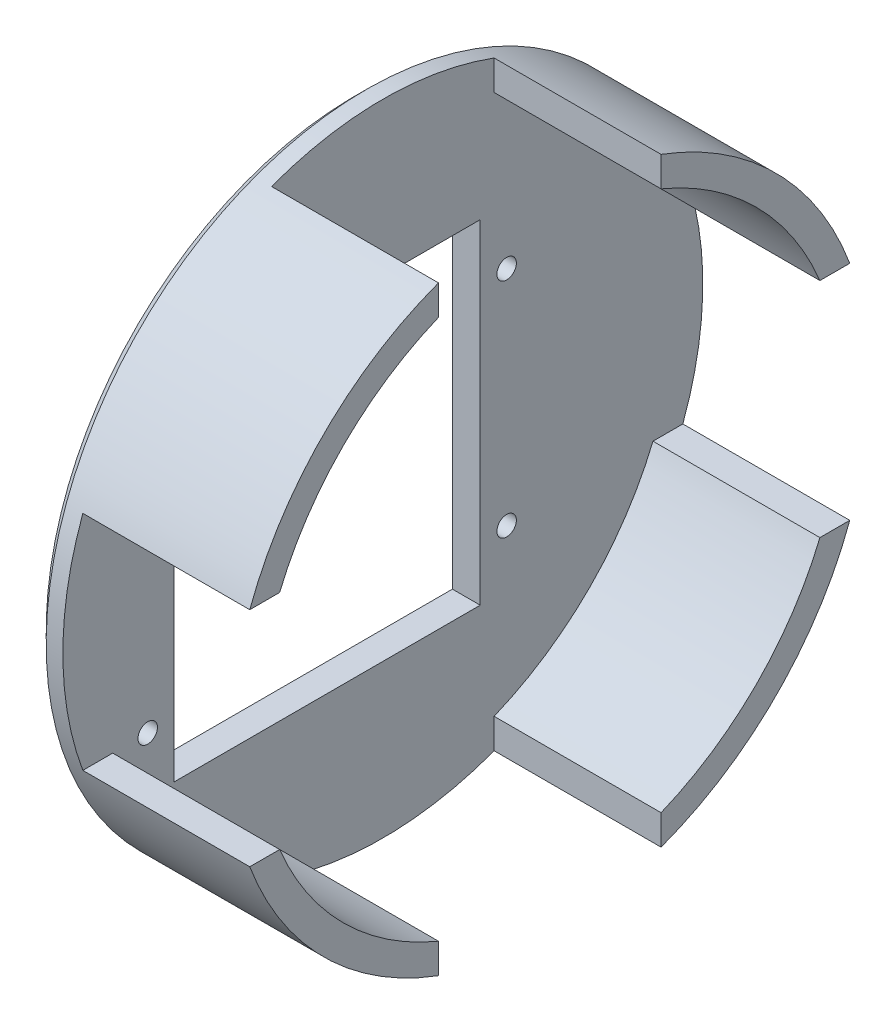
SolidWorks part; units mm, degrees
material "ﾎﾟﾘｴﾁﾚﾝｲﾐﾝ(PEI)"
ref_plane "正面" through (0, 0, 0) normal (0, 0, 1) x (1, 0, 0)
ref_plane "平面" through (0, 0, 0) normal (0, 1, 0) x (1, 0, 0)
ref_plane "右側面" through (0, 0, 0) normal (1, 0, 0) x (0, 0, -1)
sketch "ｽｹｯﾁ1" plane through (0, 0, 0) normal (1, 0, 0) x (0, 0, -1)
  circle A4 centre (0, 0) radius 57.5
  dimension "D4" = 115
extrude "ﾎﾞｽ - 押し出し1" add sketch "ｽｹｯﾁ1" along normal blind 5
sketch "ｽｹｯﾁ2" plane through (5, 0, 0) normal (1, 0, 0) x (0, 0, -1)
  circle A0 centre (0, 0) radius 52.5
  circle A1 centre (0, 0) radius 57.5
  circle A2 centre (0, 0) radius 57.5
  dimension "D1" = 0
  dimension "D2" = 5
extrude "ﾎﾞｽ - 押し出し2" add sketch "ｽｹｯﾁ2" along normal blind 30
sketch "ｽｹｯﾁ3" plane through (5, 0, 0) normal (1, 0, 0) x (0, 0, -1)
  line L0 (0, 0) -> (-10, 0) construction
  line L1 (-10, 20) -> (-10, -20) construction
  line L2 (22.25, 20) -> (-42.25, 20) construction
  line L3 (22.25, 20) -> (22.25, -20) construction
  line L4 (22.25, -20) -> (-42.25, -20) construction
  line L5 (-42.25, 20) -> (-42.25, -20) construction
  line L6 (22.25, 20) -> (-42.25, -20) construction
  line L7 (22.25, -20) -> (-42.25, 20) construction
  line L8 (-42.25, 0) -> (22.25, 0) construction
  line L14 (-37.5, 30) -> (17.5, 30)
  line L15 (-37.5, 30) -> (-37.5, -30)
  line L16 (-37.5, -30) -> (17.5, -30)
  line L17 (17.5, 30) -> (17.5, -30)
  line L18 (-37.5, 30) -> (17.5, -30) construction
  line L19 (-37.5, -30) -> (17.5, 30) construction
  circle A0 centre (-42.25, 20) radius 1.75
  circle A1 centre (-42.25, -20) radius 1.75
  circle A2 centre (22.25, 20) radius 1.75
  circle A3 centre (22.25, -20) radius 1.75
  dimension "D4" = 3.5
  dimension "D5" = 55
  dimension "D1" = 10
  dimension "D2" = 64.5
  dimension "D3" = 40
  dimension "D6" = 60
extrude "ｶｯﾄ - 押し出し1" cut sketch "ｽｹｯﾁ3" against normal through all
sketch "ｽｹｯﾁ4" plane through (35, 0, 0) normal (1, 0, 0) x (0, 0, -1)
  line L1 (-20, 53.9096) -> (20, 53.9096)
  line L2 (-20, 53.9096) -> (-20, -53.9096)
  line L3 (-20, -53.9096) -> (20, -53.9096)
  line L4 (20, 53.9096) -> (20, -53.9096)
  line L5 (-20, 53.9096) -> (20, -53.9096) construction
  line L6 (-20, -53.9096) -> (20, 53.9096) construction
  line L7 (-53.9096, 20) -> (53.9096, 20)
  line L8 (-53.9096, 20) -> (-53.9096, -20)
  line L9 (-53.9096, -20) -> (53.9096, -20)
  line L10 (53.9096, 20) -> (53.9096, -20)
  line L11 (-53.9096, 20) -> (53.9096, -20) construction
  line L12 (-53.9096, -20) -> (53.9096, 20) construction
  circle A0 centre (0, 0) radius 57.5 construction
  circle A2 centre (0, 0) radius 57.5
  circle A3 centre (0, 0) radius 57.5
  point P0 (0, 0)
  point P8 (0, 0)
  circle M4 centre (0, 0) radius 57.5
  circle M5 centre (0, 0) radius 52.5
  dimension "D1" = 40
  dimension "D2" = 0
extrude "ｶｯﾄ - 押し出し2" cut sketch "ｽｹｯﾁ4" against normal blind 30 contours L8 L9 L7 M5 | L8 M4 | L4 L1 L2 M5 | L1 M4 | L10 L7 L9 M5 | L10 M4 | L3 M4 | L4 L2 L3 M5 | A3
chamfer "面取り1" distance 2 angle 45 1 edges at (0, 0, -57.5)
